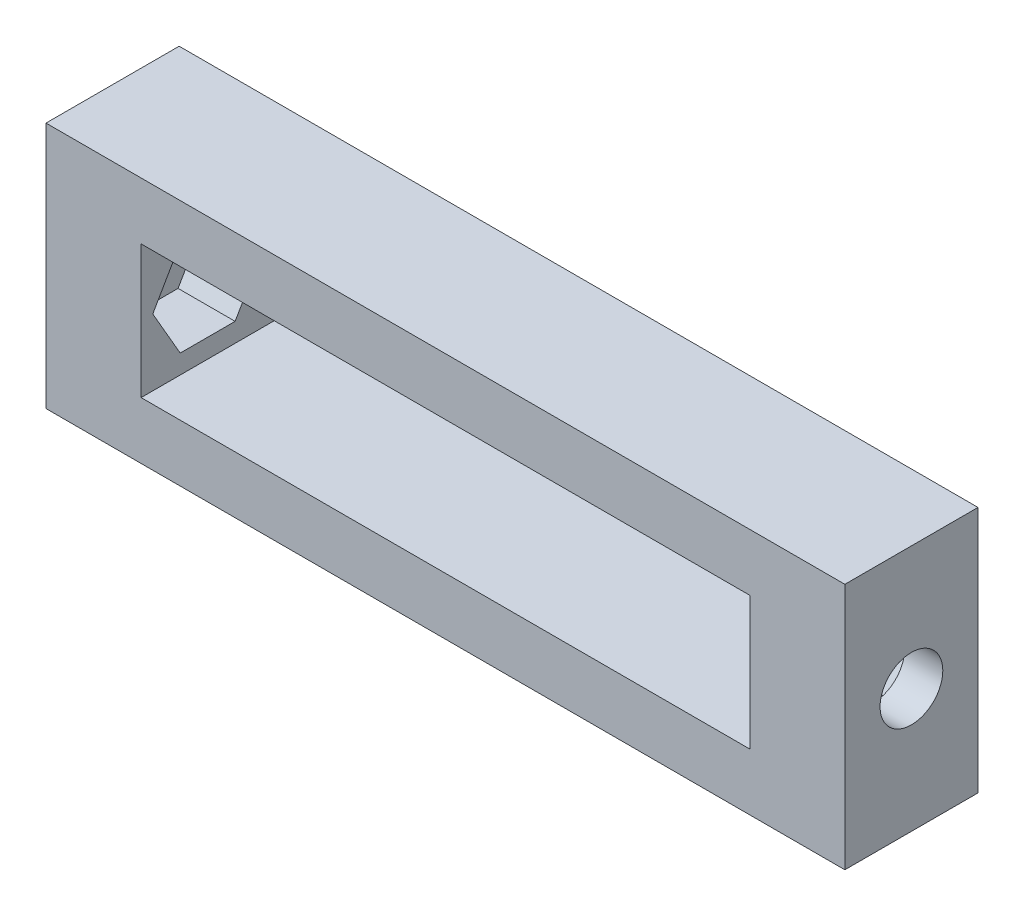
SolidWorks part; units mm, degrees
ref_plane "Plano frontal" through (0, 0, 0) normal (0, 0, 1) x (1, 0, 0)
ref_plane "Plano superior" through (0, 0, 0) normal (0, 1, 0) x (1, 0, 0)
ref_plane "Plano direito" through (0, 0, 0) normal (1, 0, 0) x (0, 0, -1)
sketch "Sketch1" plane through (0, 0, 0) normal (0, 1, 0) x (1, 0, 0)
  line L1 (-21, -3.5) -> (21, -3.5)
  line L2 (-21, -3.5) -> (-21, 3.5)
  line L3 (-21, 3.5) -> (21, 3.5)
  line L4 (21, -3.5) -> (21, 3.5)
  line L5 (-21, -3.5) -> (21, 3.5) construction
  line L6 (-21, 3.5) -> (21, -3.5) construction
  point P0 (0, 0)
  dimension "D1" = 7
  dimension "D2" = 42
extrude "Boss-Extrude1" add sketch "Sketch1" against normal blind 3 contours L1 L4 L3 L2
sketch "Sketch3" plane through (0, 0, 0) normal (0, 1, 0) x (1, 0, 0)
  line L0 (-21, -3.5) -> (21, -3.5) construction
  line L1 (-21, 3.5) -> (-16, 3.5)
  line L2 (-21, 3.5) -> (-21, -3.5)
  line L3 (-21, -3.5) -> (-16, -3.5)
  line L4 (-16, 3.5) -> (-16, -3.5)
  dimension "D1" = 5
extrude "Boss-Extrude2" add sketch "Sketch3" along normal blind 7
sketch "Sketch4" plane through (-16, 0, 0) normal (1, 0, 0) x (0, 0, -1)
  line L0 (-3.5, 7) -> (3.5, 7) construction
  line L1 (1.4434, 6) -> (-1.4434, 6)
  line L2 (-1.4434, 6) -> (-2.8868, 3.5)
  line L3 (-2.8868, 3.5) -> (-1.4434, 1)
  line L4 (-1.4434, 1) -> (1.4434, 1)
  line L5 (1.4434, 1) -> (2.8868, 3.5)
  line L6 (2.8868, 3.5) -> (1.4434, 6)
  line L7 (3.5, 7) -> (3.5, 0) construction
  circle A0 centre (0, 3.5) radius 2.5 construction
  point P1 (0, 0)
  point P11 (0, 7)
  point P14 (3.5, 3.5)
  dimension "D1" = 5
extrude "Cut-Extrude1" cut sketch "Sketch4" against normal blind 3 contours L4 L5 L6 L1 L2 L3
sketch "Sketch5" plane through (-19, 0, 0) normal (1, 0, 0) x (0, 0, -1)
  line L0 (-3.5, 7) -> (3.5, 7) construction
  line L1 (3.5, 7) -> (3.5, 0) construction
  circle A0 centre (0, 3.5) radius 1.65
  point P4 (0, 7)
  point P7 (3.5, 3.5)
  dimension "D1" = 3.3
extrude "Cut-Extrude2" cut sketch "Sketch5" against normal up to next
ref_plane "Plane1" through (0, 3.5, 0) normal (0, 1, 0) x (1, 0, 0)
mirror "Mirror3" about plane through (0, 3.5, 0) normal (0, 1, 0) of "Boss-Extrude1"
mirror "Mirror4" about plane through (0, 0, 0) normal (1, 0, 0) of "Boss-Extrude2", "Cut-Extrude1", "Cut-Extrude2"
